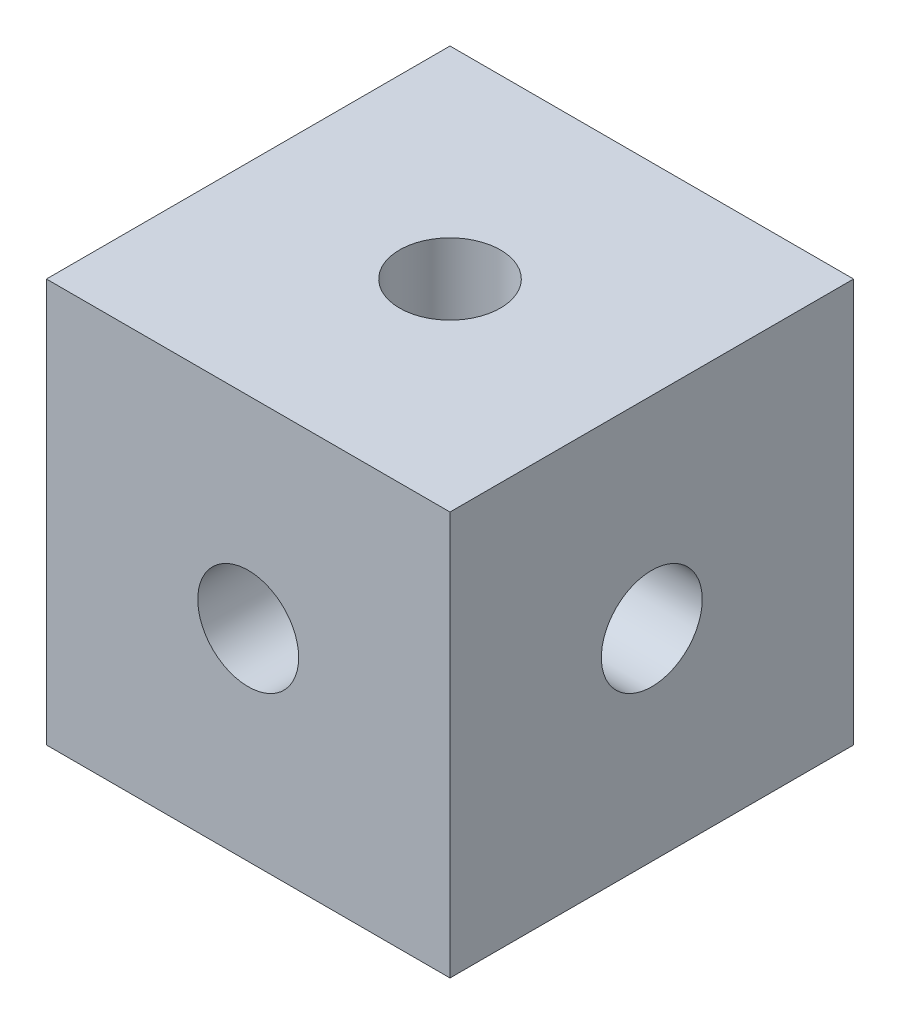
SolidWorks part; units mm, degrees
ref_plane "前视基准面" through (0, 0, 0) normal (0, 0, 1) x (1, 0, 0)
ref_plane "上视基准面" through (0, 0, 0) normal (0, 1, 0) x (1, 0, 0)
ref_plane "右视基准面" through (0, 0, 0) normal (1, 0, 0) x (0, 0, -1)
other "Configuration Table"
sketch "草图1" plane through (0, 0, 0) normal (0, 1, 0) x (1, 0, 0)
  line L1 (5, 5) -> (-5, 5)
  line L2 (5, 5) -> (5, -5)
  line L3 (5, -5) -> (-5, -5)
  line L4 (-5, 5) -> (-5, -5)
  line L5 (5, 5) -> (-5, -5) construction
  line L6 (5, -5) -> (-5, 5) construction
  point P0 (0, 0)
  dimension "D1" = 10
  dimension "D2" = 10
extrude "凸台-拉伸1" add sketch "草图1" along normal mid plane 10
hole_wizard "M3 螺纹孔1" positions "3D草图1" profile "草图2" tap size "M3" standard "GB"
sketch3d "3D草图1"
  point P0 (0, 0, 0)
  point P3 (0, 0, 0)
  point P5 (0, 0, 5)
  point P9 (0, 5, 0)
  point P11 (5, 0, 0)
  point P14 (0, 0, 0)
  point P15 (0, 0, 0)
sketch "草图2" plane through (5, 0, 0) normal (0, 1, 0) x (0, 0, -1)
  line L0 (0, 0) -> (0, 10)
  line L1 (0, 10) -> (1.25, 10)
  line L2 (1.25, 10) -> (1.25, 0)
  line L5 (1.25, 0) -> (0, 0)
  line L11 (0, -6.35) -> (0, 107.95) construction
  dimension "通孔螺纹孔钻头直径" = 2.5
  dimension "通孔螺纹孔钻头深度" = 10
cosmetic thread "孔螺蚊线1"
cosmetic thread "孔螺蚊线2"
cosmetic thread "孔螺蚊线3"
cosmetic thread "孔螺蚊线4"
cosmetic thread "孔螺蚊线5"
